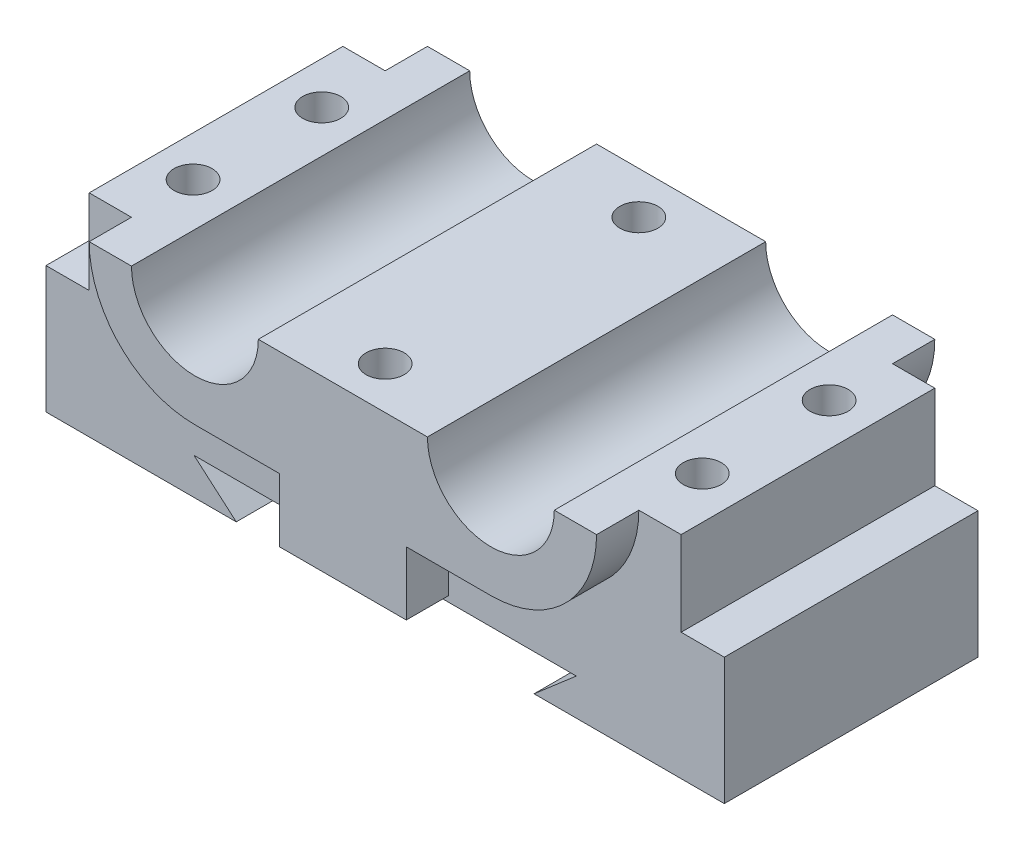
SolidWorks part; units mm, degrees
ref_plane "Front Plane" through (0, 0, 0) normal (0, 0, 1) x (1, 0, 0)
ref_plane "Top Plane" through (0, 0, 0) normal (0, 1, 0) x (1, 0, 0)
ref_plane "Right Plane" through (0, 0, 0) normal (1, 0, 0) x (0, 0, -1)
sketch "Sketch1" plane through (0, 0, 0) normal (0, 0, 1) x (1, 0, 0)
  line L0 (-17.5, 0) -> (49982.5, 0) construction
  line L1 (-30, 0) -> (-25, 0)
  line L2 (-7.5, -20) -> (-7.5, -12.5)
  line L3 (0, 0) -> (0, -50000) construction
  line L4 (7.5, -20) -> (7.5, -12.5)
  line L5 (-10, 0) -> (10, 0)
  line L6 (25, 0) -> (30, 0)
  line L7 (-17.5, -12.5) -> (-7.5, -12.5)
  line L8 (17.5, -12.5) -> (7.5, -12.5)
  line L12 (7.5, -20) -> (-7.5, -20)
  arc A0 (-25, 0) -> (-10, 0) centre (-17.5, 0) ccw
  arc A1 (10, 0) -> (25, 0) centre (17.5, 0) ccw
  arc A2 (-30, 0) -> (-17.5, -12.5) centre (-17.5, 0) ccw
  arc A3 (17.5, -12.5) -> (30, 0) centre (17.5, 0) ccw
  point P23 (0, -17.9644)
  point P29 (0, -20)
  dimension "D1" = 15
  dimension "D2" = 15
  dimension "D3" = 12.5
  dimension "D6" = 12.5
  dimension "D7" = 7.5
  dimension "D8" = 7.5
  dimension "D4" = 35
  dimension "D5" = 17.5
  dimension "D12" = 15
extrude "Boss-Extrude1" add sketch "Sketch1" along normal mid plane 40
sketch "Sketch6" plane through (0, 0, 0) normal (0, 0, 1) x (1, 0, 0)
  line L0 (-35, 0) -> (-35, -10)
  line L1 (-35, -10) -> (-40.1068, -10)
  line L2 (-40.1068, -10) -> (-40.1068, -25)
  line L3 (-40.1068, -25) -> (-17.6068, -25)
  line L4 (-17.6068, -25) -> (-22.6068, -20.6836)
  line L5 (-22.6068, -20.6836) -> (22.6068, -20.6836)
  line L6 (7.5, -12.5) -> (17.5, -12.5) construction
  line L7 (7.5, -20) -> (7.5, -12.5) construction
  line L8 (-7.5, -20) -> (7.5, -20) construction
  line L9 (-7.5, -12.5) -> (-7.5, -20) construction
  line L10 (-17.5, -12.5) -> (-7.5, -12.5) construction
  line L11 (7.5, -12.5) -> (17.5, -12.5)
  line L12 (7.5, -20) -> (7.5, -12.5)
  line L13 (-7.5, -20) -> (7.5, -20)
  line L14 (-7.5, -12.5) -> (-7.5, -20)
  line L15 (-17.5, -12.5) -> (-7.5, -12.5)
  line L16 (0, 0) -> (0, -50000) construction
  line L17 (10, 0) -> (-10, 0) construction
  line L18 (17.6068, -25) -> (22.6068, -20.6836)
  line L19 (40.1068, -25) -> (17.6068, -25)
  line L20 (40.1068, -10) -> (40.1068, -25)
  line L21 (35, -10) -> (40.1068, -10)
  line L22 (35, 0) -> (35, -10)
  line L23 (-35, 0) -> (-30, 0)
  line L24 (30, 0) -> (35, 0)
  arc A0 (17.5, -12.5) -> (30, 0) centre (17.5, 0) ccw construction
  arc A1 (-30, 0) -> (-17.5, -12.5) centre (-17.5, 0) ccw construction
  arc A2 (17.5, -12.5) -> (30, 0) centre (17.5, 0) ccw
  arc A3 (-30, 0) -> (-17.5, -12.5) centre (-17.5, 0) ccw
  point P21 (0, 0)
  point P23 (0, -20.6836)
  dimension "D1" = 17.5
  dimension "D2" = 10
  dimension "D3" = 15
  dimension "D4" = 22.5
  dimension "D5" = 5
extrude "Boss-Extrude2" add sketch "Sketch6" along normal mid plane 30
hole_wizard "Ø3.0mm Dowel Hole1" positions "Sketch7" profile "Sketch8" hole size "Ø3.0" standard "ISO"
sketch "Sketch7" plane through (0, 0, 0) normal (0, 1, 0) x (1, 0, 0)
  line L0 (-30, 15) -> (-30, 20) construction
  line L1 (-30, 15) -> (-35, 15) construction
  line L2 (30, 15) -> (30, 20) construction
  line L3 (40.1068, 15) -> (35, 15) construction
  point P0 (0, 15)
  point P2 (0, -15)
  point P4 (30, 7.5)
  point P6 (30, -7.5)
  point P21 (-30, 7.5)
  point P23 (-30.2157, -7.5)
  dimension "D1" = 30
  dimension "D2" = 0
  dimension "D3" = 30
  dimension "D4" = 0
  dimension "D5" = 15
  dimension "D6" = 7.5
  dimension "D7" = 0
sketch "Sketch8" plane through (0, 0, -15) normal (1, 0, 0) x (0, 0, 1)
  line L0 (0, 0) -> (0, 16.3519)
  line L1 (0, 16.3519) -> (2.25, 15)
  line L2 (2.25, 15) -> (2.25, 0)
  line L5 (2.25, 0) -> (0, 0)
  line L10 (0, 16.3519) -> (-2.25, 15) construction
  line L11 (0, -6.35) -> (0, 107.95) construction
  dimension "Hole Dia." = 4.5
  dimension "Hole Depth" = 15
  dimension "Drill Angle" = 118
